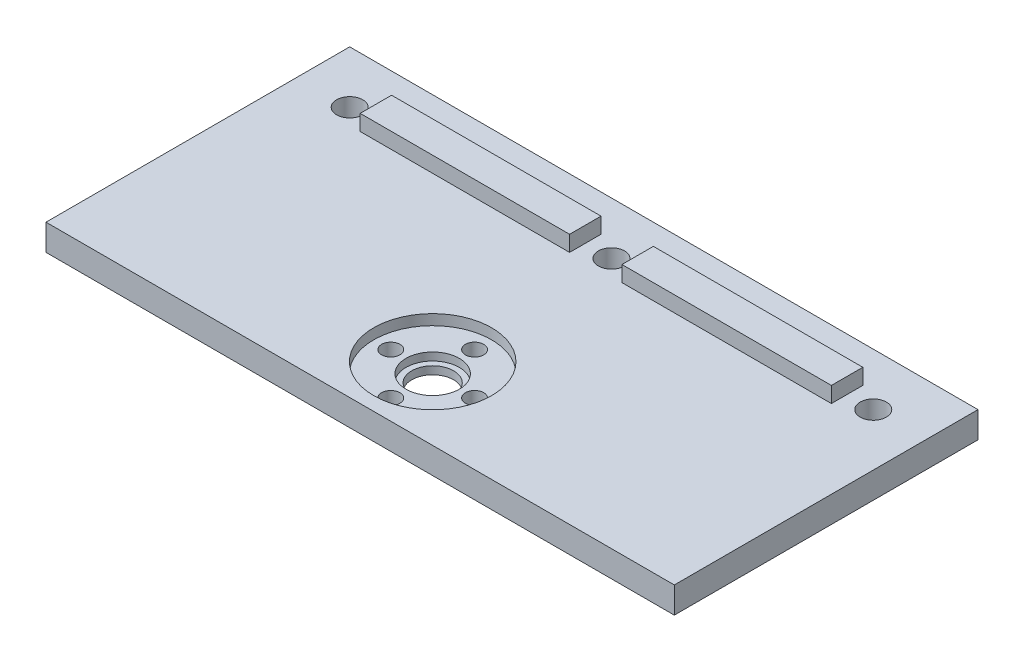
SolidWorks part; units mm, degrees
ref_plane "Front Plane" through (0, 0, 0) normal (0, 0, 1) x (1, 0, 0)
ref_plane "Top Plane" through (0, 0, 0) normal (0, 1, 0) x (1, 0, 0)
ref_plane "Right Plane" through (0, 0, 0) normal (1, 0, 0) x (0, 0, -1)
sketch "Sketch1" plane through (0, 0, 0) normal (0, 1, 0) x (1, 0, 0)
  line L1 (0, 0) -> (120, 0)
  line L2 (0, 0) -> (0, 58)
  line L3 (0, 58) -> (120, 58)
  line L4 (120, 0) -> (120, 58)
  point P6 (0, 0)
  point P7 (0, 0)
  point P8 (0, 0)
  point P9 (0, 0)
  point P10 (0, 0)
  point P11 (0, 0)
  point P12 (0, 0)
  point P13 (0, 0)
  point P14 (0, 0)
  point P15 (0, 0)
  point P16 (0, 0)
  point P17 (0, 0)
  point P18 (99.8191, 0)
  point P19 (0, 0)
  point P20 (0, 0)
  point P21 (0, 0)
  point P22 (0, 0)
  point P23 (0, 0)
extrude "Boss-Extrude5" add sketch "Sketch1" along normal blind 5
sketch "Sketch5" plane through (0, 5, 0) normal (0, 1, 0) x (1, 0, 0)
  circle A0 centre (10, 48) radius 2.5
  circle A1 centre (60, 48) radius 2.5
  circle A2 centre (110, 48) radius 2.5
extrude "Cut-Extrude2" cut sketch "Sketch5" against normal blind 5
sketch "Sketch6" plane through (0, 5, 0) normal (0, 1, 0) x (1, 0, 0)
  line L1 (15, 45) -> (55, 45)
  line L2 (15, 45) -> (15, 51)
  line L3 (15, 51) -> (55, 51)
  line L4 (55, 45) -> (55, 51)
  line L5 (65, 45) -> (105, 45)
  line L6 (65, 45) -> (65, 51)
  line L7 (65, 51) -> (105, 51)
  line L8 (105, 45) -> (105, 51)
  point P8 (0, 0)
  point P9 (0, 0)
  point P10 (0, 0)
  point P11 (0, 0)
  point P12 (0, 0)
  point P13 (0, 0)
  point P14 (0, 0)
extrude "Boss-Extrude6" add sketch "Sketch6" along normal blind 3
sketch "Sketch7" plane through (0, 5, 0) normal (0, 1, 0) x (1, 0, 0)
  circle A6 centre (60, 13.85) radius 11.25
  circle A8 centre (110, 48) radius 2.5 construction
  point P0 (0, 0)
  dimension "D1" = 34.15
extrude "Cut-Extrude3" cut sketch "Sketch7" against normal blind 2
sketch "Sketch8" plane through (0, 3, 0) normal (0, 1, 0) x (1, 0, 0)
  circle A0 centre (60, 13.85) radius 4
extrude "Cut-Extrude4" cut sketch "Sketch8" against normal blind 12
sketch "Sketch9" plane through (0, 3, 0) normal (0, 1, 0) x (1, 0, 0)
  circle A0 centre (60, 13.85) radius 5.1
extrude "Cut-Extrude5" cut sketch "Sketch9" against normal blind 1.5
sketch "Sketch10" plane through (0, 3, 0) normal (0, 1, 0) x (1, 0, 0)
  circle A0 centre (52, 13.85) radius 1.75
  circle A1 centre (60, 21.85) radius 1.75
  circle A2 centre (68, 13.85) radius 1.75
  circle A3 centre (60, 5.85) radius 1.75
extrude "Cut-Extrude6" cut sketch "Sketch10" against normal blind 21.5
